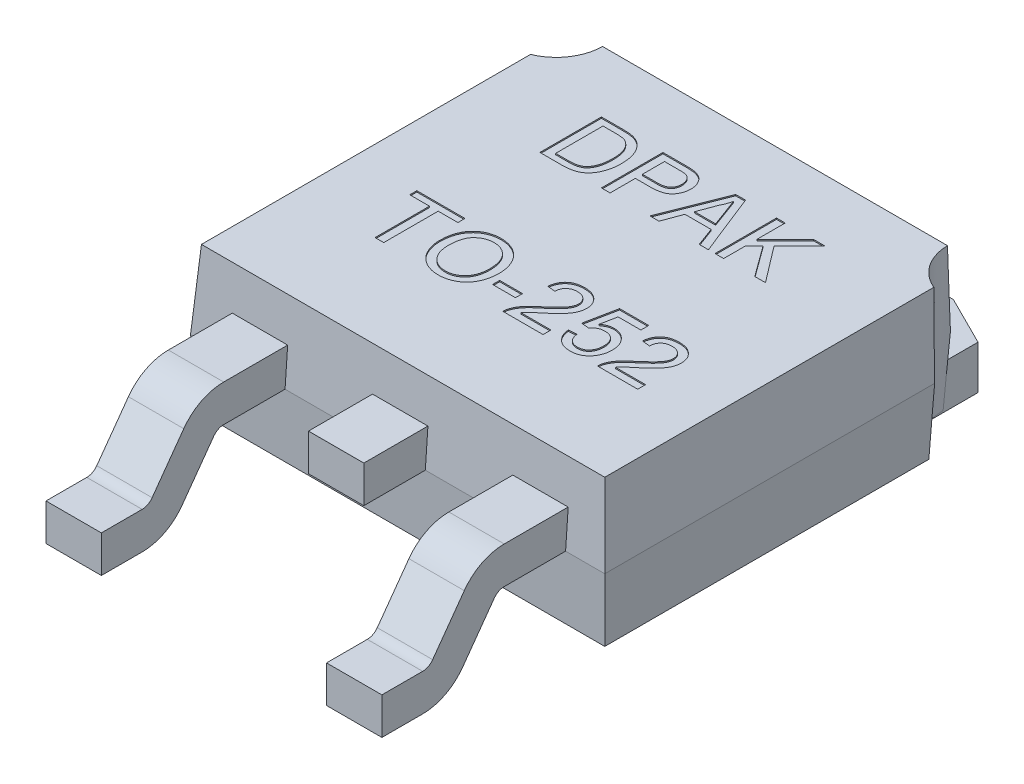
SolidWorks part; units mm, degrees
ref_plane "Front Plane" through (0, 0, 0) normal (0, 0, 1) x (1, 0, 0)
ref_plane "Top Plane" through (0, 0, 0) normal (0, 1, 0) x (1, 0, 0)
ref_plane "Right Plane" through (0, 0, 0) normal (1, 0, 0) x (0, 0, -1)
sketch "Sketch1" plane through (0, 0, 0) normal (0, 1, 0) x (1, 0, 0)
  line L0 (3.29, -3.035) -> (3.29, 3.035)
  line L1 (3.29, 0) -> (-3.29, 0) construction
  line L2 (0, 0) -> (0, 3.035) construction
  line L3 (3.29, 3.035) -> (-3.29, 3.035)
  line L4 (-3.29, -3.035) -> (-3.29, 3.035)
  line L5 (3.29, -3.035) -> (-3.29, -3.035)
  dimension "D1" = 3.29
  dimension "D2" = 3.035
extrude "Boss-Extrude1" add sketch "Sketch1" along normal blind 1.1 draft 4 draft outward yes
sketch "Sketch2" plane through (0, 0, 0) normal (0, 1, 0) x (1, 0, 0)
  line L0 (0, 0) -> (0, 5.0647) construction
  line L1 (0, 0) -> (-5.6064, 0) construction
  line L3 (2.72, 0) -> (2.72, 3.6019)
  line L4 (3.3669, 4.0019) -> (-3.3669, 4.0019)
  line L5 (1.92, 4.0019) -> (-1.92, 4.0019)
  line L6 (-2.72, 0) -> (-2.72, 3.6019)
  line L7 (-2.72, 0) -> (-2.72, 5.0647) construction
  line L8 (2.72, -1.4981) -> (-2.72, -1.4981)
  line L9 (-2.72, 3.6019) -> (-1.92, 4.0019)
  line L10 (2.72, 0) -> (2.72, 5.0647) construction
  line L11 (2.72, 3.6019) -> (1.92, 4.0019)
  line L12 (-2.72, 0) -> (-2.72, -1.4981)
  line L13 (2.72, 0) -> (2.72, -1.4981)
  line L14 (1.92, -1.4981) -> (-1.92, -1.4981) construction
  point P12 (-2.72, 4.0019)
  point P15 (-2.72, 4.0019)
  point P18 (2.72, 4.0019)
  dimension "D1" = 0.89
  dimension "D4" = 5.5
  dimension "D5" = 0.8
  dimension "D6" = 0.8
  dimension "D7" = 0.4
  dimension "D8" = 0.4
  dimension "D2" = 2.72
  dimension "D3" = 2.72
extrude "Boss-Extrude2" add sketch "Sketch2" along normal blind 0.68 and the other way blind 0.03
sketch "Sketch3" plane through (0, 0, 0) normal (0, 1, 0) x (1, 0, 0)
  line L0 (0, 4.0019) -> (0, 2.8387) construction
  line L1 (1.92, 4.0019) -> (-1.92, 4.0019) construction
  line L2 (-1, 4.0019) -> (-1, 3.6756)
  line L3 (1, 4.0019) -> (1, 3.6756)
  line L4 (-0.95, 3.6256) -> (0.95, 3.6256)
  line L5 (-1, 4.0019) -> (-1, 2.8387) construction
  line L6 (1, 4.0019) -> (1, 2.8387) construction
  line L7 (-1, 4.0019) -> (1, 4.0019)
  arc A0 (-0.95, 3.6256) -> (-1, 3.6756) centre (-0.95, 3.6756) cw
  arc A1 (1, 3.6756) -> (0.95, 3.6256) centre (0.95, 3.6756) cw
  dimension "D3" = 0.05
  dimension "D4" = 0.05
  dimension "D1" = 1
  dimension "D2" = 1
extrude "Cut-Extrude1" cut sketch "Sketch3" along normal through all and the other way through all
sketch "Sketch4" plane through (0, -0.03, 0) normal (0, -1, 0) x (1, 0, 0)
  line L0 (0, 0) -> (0, -4.211) construction
  line L1 (0, -2.1055) -> (-1, -2.1055) construction
  line L2 (0, -1.8555) -> (-1, -1.8555)
  line L3 (0, -2.3555) -> (-1, -2.3555)
  line L4 (0, -2.1055) -> (1, -2.1055) construction
  line L5 (0, -2.3555) -> (1, -2.3555)
  line L6 (0, -1.8555) -> (1, -1.8555)
  line L7 (-2.5, 1.4981) -> (-2.5, -2.3555)
  line L8 (2.5, 1.4981) -> (2.5, -2.3555)
  line L9 (-2.5, 0) -> (-2.5, -4.211) construction
  line L10 (-2.72, 1.4981) -> (2.72, 1.4981) construction
  line L11 (2.5, 0) -> (2.5, -4.211) construction
  line L12 (-2.72, -2.3555) -> (-2.5, -2.3555)
  line L13 (-2.72, -3.6019) -> (-2.72, 1.4981) construction
  line L14 (2.5, -2.3555) -> (2.72, -2.3555)
  line L15 (2.72, 1.4981) -> (2.72, -3.6019) construction
  line L16 (-2.72, -2.3555) -> (-2.72, 1.4981)
  line L17 (-2.72, 1.4981) -> (-2.5, 1.4981)
  line L18 (2.72, -2.3555) -> (2.72, 1.4981)
  line L19 (2.72, 1.4981) -> (2.5, 1.4981)
  arc A0 (-1, -2.3555) -> (-1, -1.8555) centre (-0.9917, -2.1055) cw
  arc A1 (1, -2.3555) -> (1, -1.8555) centre (0.9917, -2.1055) ccw
  dimension "D3" = 1
  dimension "D1" = 0.25
  dimension "D2" = 0.25
  dimension "D4" = 2.5
  dimension "D5" = 2.5
extrude "Cut-Extrude2" cut sketch "Sketch4" against normal blind 0.03
sketch "Sketch5" plane through (0, 0, 0) normal (1, 0, 0) x (0, 0, -1)
  line L0 (0, 1.1) -> (-4.1095, 1.1)
  line L1 (3.1119, 1.1) -> (-3.1119, 1.1) construction
  line L2 (0, 1.7) -> (-4.1095, 1.7)
  line L3 (-4.7587, 1.3674) -> (-5.5465, 0.2731) construction
  line L4 (-5.4353, -0.03) -> (-6.0981, -0.03)
  line L5 (-6.0981, -0.03) -> (-6.0981, 0.68)
  line L6 (-6.0981, -0.03) -> (-6.0981, 0.57)
  line L7 (-5.4353, 0.57) -> (-6.0981, 0.57)
  line L8 (-5.4981, -0.03) -> (-5.4981, 0.57) construction
  line L9 (-3.1119, 1.1) -> (-3.1119, -1.3356) construction
  line L10 (-4.2119, 1.1) -> (-4.2119, -1.3356) construction
  line L11 (-4.2718, 1.0169) -> (-4.786, 0.3026)
  line L12 (-4.7587, 1.3674) -> (-5.273, 0.6531)
  line L13 (0, 1.1) -> (-4.6483, 1.1) construction
  line L14 (0, 1.7) -> (-4.6483, 1.7) construction
  line L15 (-1.4981, -0.03) -> (-6.0981, -0.03) construction
  line L16 (-4.2718, 1.0169) -> (-5.0596, -0.0774) construction
  line L17 (-1.4981, 0.57) -> (-6.0981, 0.57) construction
  line L18 (0, 1.7) -> (0, 1.1)
  arc A0 (-4.2718, 1.0169) -> (-4.1095, 1.1) centre (-4.1095, 0.9) cw
  arc A1 (-4.7587, 1.3674) -> (-4.1095, 1.7) centre (-4.1095, 0.9) cw
  arc A2 (-5.4353, -0.03) -> (-4.786, 0.3026) centre (-5.4353, 0.77) ccw
  arc A3 (-5.273, 0.6531) -> (-5.4353, 0.57) centre (-5.4353, 0.77) cw
  dimension "D6" = 0.2
  dimension "D8" = 0.8
  dimension "D9" = 0.8
  dimension "D10" = 0.2
  dimension "D1" = 0.6
  dimension "D3" = 0.6
  dimension "D5" = 1.1
  dimension "D2" = 10.1
  dimension "D4" = 0.6
  dimension "D7" = 0.6
extrude "Boss-Extrude3" add sketch "Sketch5" along normal blind 0.45 and the other way blind 0.45
pattern_linear "LPattern1" count 2 spacing 2.28 along (1, 0, 0) count 2 spacing 2.28 along (-1, 0, 0) of "Boss-Extrude3"
sketch "Sketch6" plane through (0, 1.7, 0) normal (0, 1, 0) x (1, 0, 0)
  line L1 (-0.655, -4.1119) -> (-0.655, -6.3161)
  line L2 (-1.83, -4.1119) -> (-0.45, -4.1119)
  line L3 (-0.655, -4.1119) -> (0.6733, -4.1119)
  line L4 (-0.655, -6.3161) -> (0.6733, -6.3161)
  line L5 (0.6733, -6.3161) -> (0.6733, -4.1119)
  dimension "D1" = 1
extrude "Cut-Extrude3" cut sketch "Sketch6" against normal through all
sketch "Sketch7" plane through (0, 1.1, 0) normal (0, 1, 0) x (1, 0, 0)
  line L0 (3.3669, 3.1119) -> (-3.3669, 3.1119) construction
  line L1 (-3.3669, 3.1119) -> (-3.3669, -3.1119) construction
  line L2 (3.3669, -3.1119) -> (3.3669, 3.1119) construction
  line L3 (-3.3669, -3.1119) -> (-2.73, -3.1119) construction
  line L4 (3.3669, 3.1119) -> (-3.3669, 3.1119)
  line L5 (-3.3669, 3.1119) -> (-3.3669, -3.1119)
  line L6 (3.3669, -3.1119) -> (3.3669, 3.1119)
  line L7 (-3.3669, -3.1119) -> (3.3669, -3.1119)
extrude "Boss-Extrude4" add sketch "Sketch7" along normal offset from surface 2.4 draft 4 up to face at (0, -0.03, -2.7637)
sketch "Sketch8" plane through (0, 2.37, 0) normal (0, 1, 0) x (1, 0, 0)
  text T0 " DPAK\r\nTO-252" font "Arial" height 1
extrude "Cut-Extrude4" cut sketch "Sketch8" against normal blind 0.02
sketch "Sketch9" plane through (0, 0, 0) normal (0, -1, 0) x (1, 0, 0)
  line L0 (0, 0) -> (0, -3.9474) construction
  circle A0 centre (-3.5689, -3.035) radius 0.8489
  circle A1 centre (3.5689, -3.035) radius 0.8489
extrude "Cut-Extrude7" cut sketch "Sketch9" against normal through all draft 2
